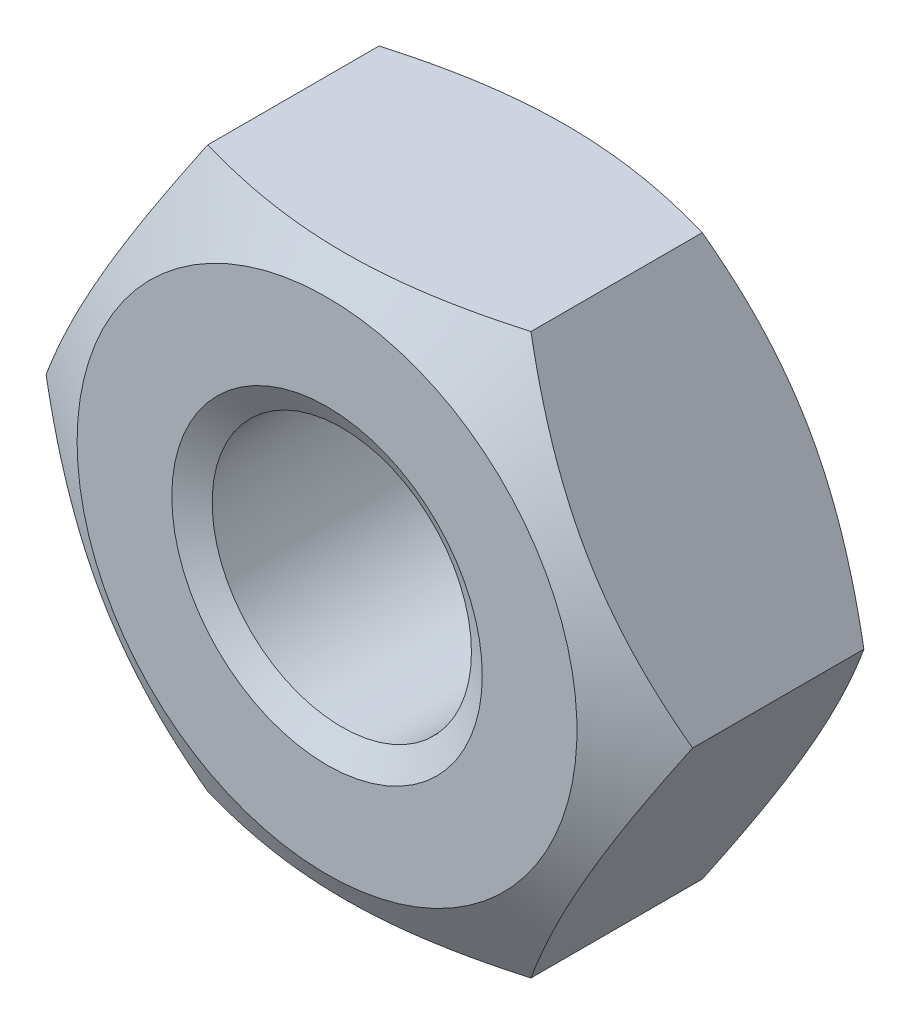
SolidWorks part; units mm, degrees
ref_plane "Front" through (0, 0, 0) normal (0, 0, 1) x (1, 0, 0)
ref_plane "Top" through (0, 0, 0) normal (0, 1, 0) x (1, 0, 0)
ref_plane "Right" through (0, 0, 0) normal (1, 0, 0) x (0, 0, -1)
sketch "Sketch1" plane through (0, 0, 0) normal (0, 0, 1) x (1, 0, 0)
  line L1 (2.0207, -3.5) -> (4.0415, 0)
  line L2 (4.0415, 0) -> (2.0207, 3.5)
  line L3 (2.0207, 3.5) -> (-2.0207, 3.5)
  line L4 (-2.0207, 3.5) -> (-4.0415, 0)
  line L5 (-4.0415, 0) -> (-2.0207, -3.5)
  line L6 (-2.0207, -3.5) -> (2.0207, -3.5)
  circle A0 centre (0, 0) radius 3.5 construction
  circle A1 centre (0, 0) radius 1.621
  dimension "D" = 3.242
  dimension "s" = 7
extrude "BaseNut" add sketch "Sketch1" against normal blind 3.2
cosmetic thread "ThreadCosmetic1" parameters "D"=4
sketch "Sketch2" plane through (0, 0, 0) normal (0, 1, 0) x (1, 0, 0)
  line L0 (-4.0415, 3.2) -> (-3.125, 3.2)
  line L2 (-3.125, 3.2) -> (-4.0415, 2.6709)
  line L3 (-4.0415, 2.6709) -> (-4.0415, 3.2)
  line L4 (0, 3.3759) -> (0, -9.8171) construction
  line L6 (-9.7712, 1.6) -> (9.8853, 1.6) construction
  line L7 (-4.0415, 0.5291) -> (-4.0415, 0)
  line L8 (-3.125, 0) -> (-4.0415, 0.5291)
  line L9 (-4.0415, 0) -> (-3.125, 0)
  dimension "dw" = 6.25
  dimension "D1" = 30
  dimension "D2" = 1.6
revolve "Double-Chamfer" cut sketch "Sketch2" angle 360 about L4
chamfer "EndChamfer" distance 0.32 angle 30 2 edges at (1.621, 0, -3.2) (1.621, 0, 0)
sketch "Sketch3" plane through (0, 0, 0) normal (0, 1, 0) x (1, 0, 0)
  line L0 (0, 6.7075) -> (0, -2.1252) construction
  line L1 (1.242, 3.0695) -> (1.621, 3.0695)
  line L2 (1.621, 3.0695) -> (1.9492, 2.88)
  line L3 (1.9492, 2.88) -> (1.621, 2.6905)
  line L4 (1.621, 2.6905) -> (1.242, 2.6905)
  line L5 (1.242, 2.6905) -> (1.242, 3.0695)
  line L6 (1.621, 2.88) -> (-1.621, 2.88) construction
  dimension "D1" = 0.379
  dimension "D2" = 3.242
revolve "Cut-Revolve10" [suppressed] cut sketch "Sketch3" angle 360 about L0
pattern_linear "LPattern10" [suppressed] count 6 spacing 0.4548 along (0, 0, 1)
equation "\"dw@Sketch2\" = \"s@Sketch1\"-0.75"
equation "\"D2@Sketch2\" = \"m@BaseNut\" / 2"
equation "\"D1@EndChamfer\" = \"m@BaseNut\" / 10"
equation "\"D2@Sketch3\" = \"D@Sketch1\""
equation "\"D1@Sketch3\" = (  \"D@ThreadCosmetic1\" - \"D@Sketch1\" )  / 2"
equation "\"D3@LPattern10\" = \"D1@Sketch3\" * 1.2"
equation "\"D1@LPattern10\" = (  \"m@BaseNut\" - \"D1@EndChamfer\" )  / \"D3@LPattern10\" "
